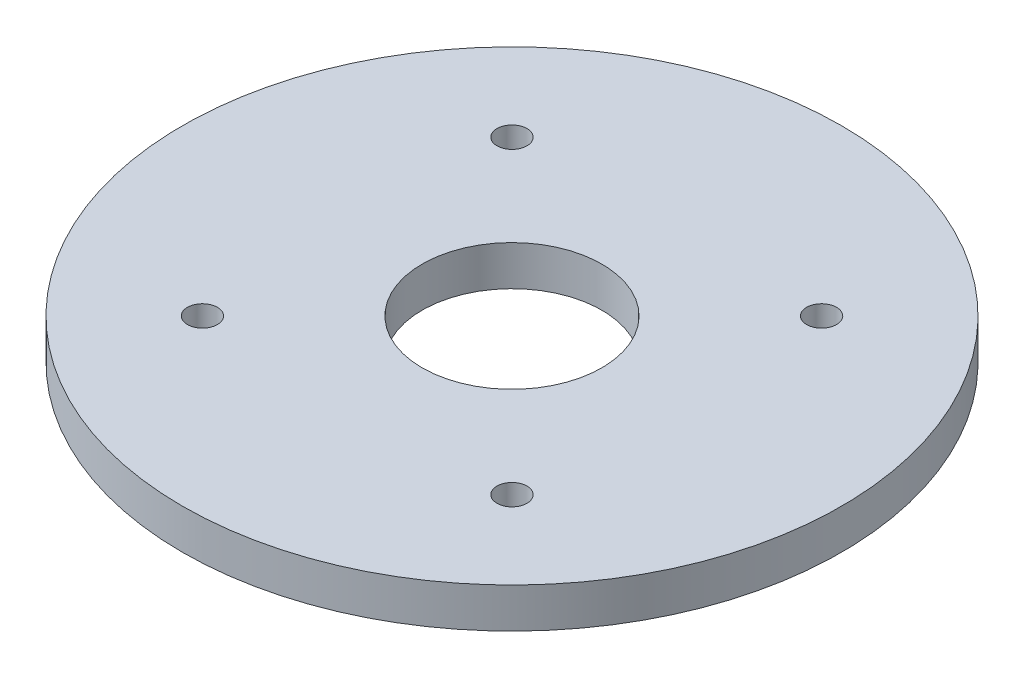
SolidWorks part; units mm, degrees
ref_plane "Front Plane" through (0, 0, 0) normal (0, 0, 1) x (1, 0, 0)
ref_plane "Top Plane" through (0, 0, 0) normal (0, 1, 0) x (1, 0, 0)
ref_plane "Right Plane" through (0, 0, 0) normal (1, 0, 0) x (0, 0, -1)
sketch "Sketch1" plane through (0, 0, 0) normal (0, 1, 0) x (1, 0, 0)
  line L1 (-15.5, 15.5) -> (15.5, 15.5)
  line L2 (-15.5, 15.5) -> (-15.5, -15.5)
  line L3 (-15.5, -15.5) -> (15.5, -15.5)
  line L4 (15.5, 15.5) -> (15.5, -15.5)
  line L5 (-15.5, 15.5) -> (15.5, -15.5) construction
  line L6 (-15.5, -15.5) -> (15.5, 15.5) construction
  circle A0 centre (0, 0) radius 33
  circle A1 centre (-15.5, 15.5) radius 1.5
  circle A2 centre (15.5, 15.5) radius 1.5
  circle A3 centre (-15.5, -15.5) radius 1.5
  circle A4 centre (15.5, -15.5) radius 1.5
  circle A5 centre (0, 0) radius 9
  dimension "D1" = 66
  dimension "D4" = 3
  dimension "D5" = 3
  dimension "D6" = 3
  dimension "D7" = 3
  dimension "D8" = 18
  dimension "D2" = 31
  dimension "D3" = 31
extrude "Boss-Extrude1" add sketch "Sketch1" along normal blind 4 contours A0 A4 L3 A3 L2 A1 L1 A2 L4 | A4 L4 A2 L1 A1 L2 A3 L3 A5
